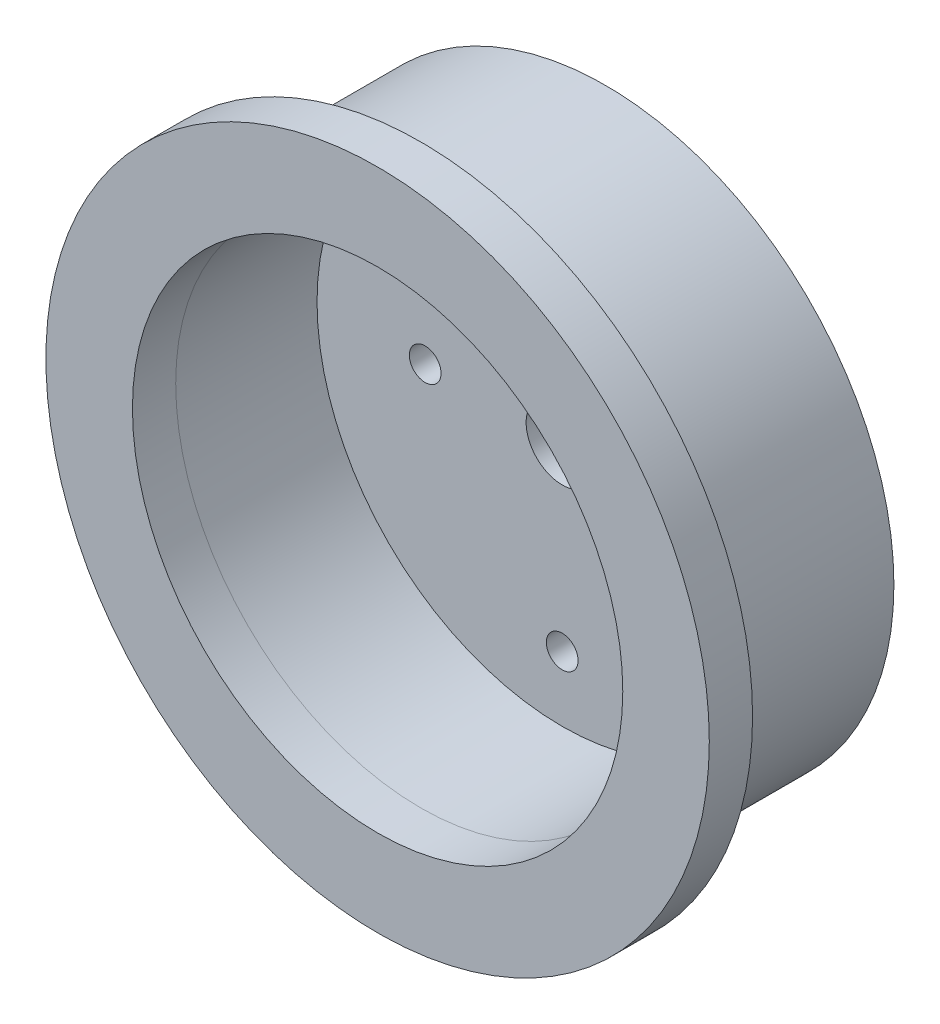
SolidWorks part; units mm, degrees
material "1345 合金"
ref_plane "前视基准面" through (0, 0, 0) normal (0, 0, 1) x (1, 0, 0)
ref_plane "上视基准面" through (0, 0, 0) normal (0, 1, 0) x (1, 0, 0)
ref_plane "右视基准面" through (0, 0, 0) normal (1, 0, 0) x (0, 0, -1)
sketch "草图1" plane through (0, 0, 0) normal (0, 0, 1) x (1, 0, 0)
  circle A0 centre (0, 0) radius 20
  dimension "D1" = 40
extrude "凸台-拉伸1" add sketch "草图1" along normal blind 12.8
sketch "草图2" plane through (0, 0, 12.8) normal (0, 0, 1) x (1, 0, 0)
  circle A0 centre (0, 0) radius 17
  dimension "D1" = 34
extrude "切除-拉伸1" cut sketch "草图2" against normal blind 9.8
sketch "草图3" plane through (0, 0, 12.8) normal (0, 0, 1) x (1, 0, 0)
  circle A0 centre (0, 0) radius 23
  circle A2 centre (0, 0) radius 17 construction
  circle A3 centre (0, 0) radius 17
  dimension "D1" = 46
extrude "凸台-拉伸2" add sketch "草图3" along normal blind 3 separate body
sketch "草图4" plane through (0, 0, 3) normal (0, 0, 1) x (1, 0, 0)
  circle A0 centre (0, 0) radius 12.5 construction
  circle A1 centre (0, 0) radius 9.5 construction
  circle A2 centre (0, -12.5) radius 1.1
  circle A3 centre (0, 12.5) radius 1.1
  circle A4 centre (9.5, 0) radius 1.1
  circle A5 centre (-9.5, 0) radius 1.1
  dimension "D1" = 25
  dimension "D2" = 19
  dimension "D3" = 2.2
extrude "切除-拉伸2" cut sketch "草图4" against normal through all
sketch "草图5" plane through (0, 0, 3) normal (0, 0, 1) x (1, 0, 0)
  circle A0 centre (0, 0) radius 16 construction
  circle A1 centre (2.7764, -15.7573) radius 1.05
  circle A2 centre (0, -12.5) radius 1.1 construction
  circle A3 centre (0, -12.5) radius 1.1 construction
  circle A4 centre (-15.0344, 5.4742) radius 1.05
  circle A5 centre (0, 0) radius 16 construction
  circle A6 centre (12.258, 10.2831) radius 1.05
  circle A7 centre (0, 0) radius 16 construction
  point P17 (0, 0)
  dimension "D1" = 32
  dimension "D2" = 2.1
  dimension "D3" = 4.28
  dimension "D4" = 3
extrude "切除-拉伸3" [suppressed] cut sketch "草图5" against normal through all
sketch "草图6" plane through (0, 0, 3) normal (0, 0, 1) x (1, 0, 0)
  circle A0 centre (0, 0) radius 2.5
  dimension "D1" = 5
extrude "切除-拉伸4" cut sketch "草图6" against normal blind 10
